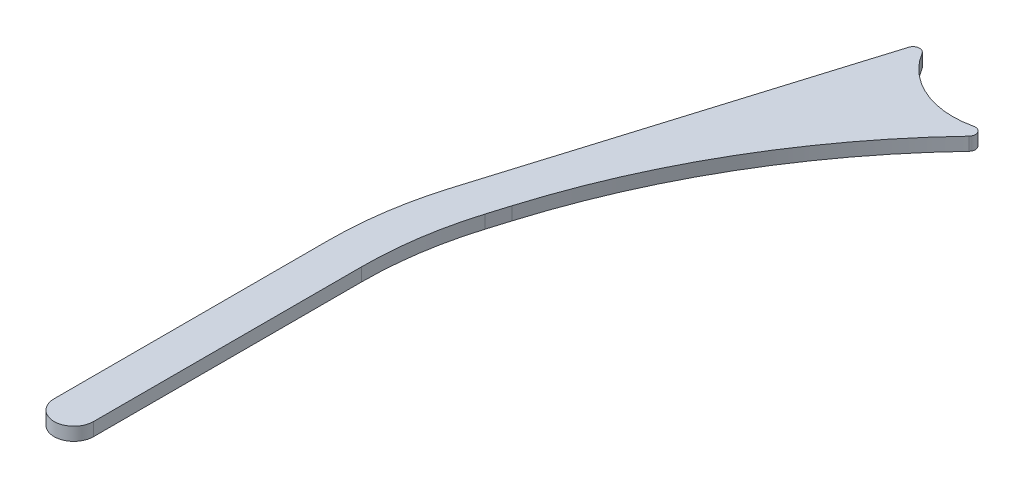
SolidWorks part; units mm, degrees
material "Acrylic (Medium-high impact)"
ref_plane "Front Plane" through (0, 0, 0) normal (0, 0, 1) x (1, 0, 0)
ref_plane "Top Plane" through (0, 0, 0) normal (0, 1, 0) x (1, 0, 0)
ref_plane "Right Plane" through (0, 0, 0) normal (1, 0, 0) x (0, 0, -1)
sketch "Sketch1" plane through (0, 0, 0) normal (0, 1, 0) x (1, 0, 0)
  line L2 (-99.0206, -242.4276) -> (-99.0206, -374.65)
  line L5 (-99.0206, -374.65) -> (-79.9706, -374.65) construction
  line L8 (-79.9706, -245.2669) -> (-79.9706, -374.65)
  line L11 (-91.2929, -190.5791) -> (-39.6864, -21.3006)
  line L13 (-69.1617, -183.3118) -> (-72.2429, -193.4184)
  line L14 (-79.9706, -218.7668) -> (-98.1926, -213.2116) construction
  line L15 (27.0899, -29.0041) -> (41.0118, -16.0009) construction
  arc A4 (-79.9706, -374.65) -> (-99.0206, -374.65) centre (-89.4956, -374.65) cw
  arc A7 (-33.9346, -20.5801) -> (9.0253, -38.6477) centre (0, 0) ccw
  arc A8 (-91.2929, -190.5791) -> (-99.0206, -242.4276) centre (78.7794, -242.4276) ccw
  arc A9 (-72.2429, -193.4184) -> (-79.9706, -245.2669) centre (97.8294, -245.2669) ccw
  arc A10 (-39.6864, -21.3006) -> (-33.9346, -20.5801) centre (-36.6494, -22.2265) cw
  arc A11 (-69.1617, -183.3118) -> (12.0504, -43.925) centre (266.9062, -285.7659) cw
  arc A12 (9.0253, -38.6477) -> (12.0504, -43.925) centre (9.7473, -41.7395) cw
  circle A13 centre (0, 0) radius 37.465 construction
  circle A14 centre (0, 0) radius 31.75 construction
  dimension "D5" = 3.175
  dimension "D3" = 39.6875
  dimension "D4" = 30
  dimension "D7" = 74.93
  dimension "D8" = 63.5
  dimension "D9" = 374.65
  dimension "D11" = 177.8
  dimension "D1" = 19.05
  dimension "D2" = 163.046
  dimension "D10" = 89.4956
extrude "Boss-Extrude1" add sketch "Sketch1" along normal blind 6.35
ref_plane "Plane1" through (-89.4956, 6.35, 384.175) normal (0, 0, 1) x (1, 0, 0)
